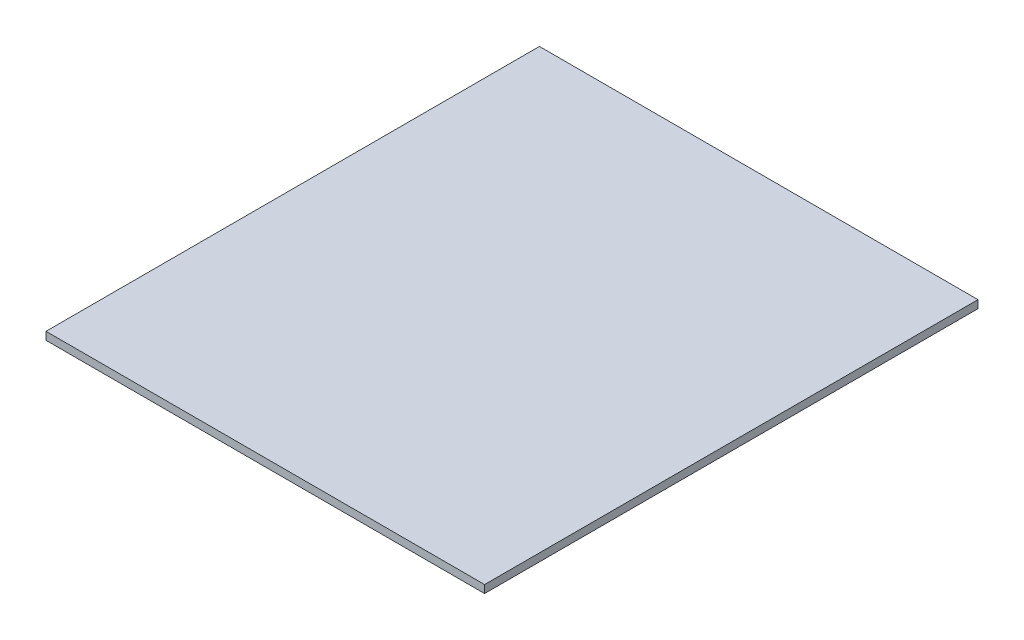
SolidWorks part; units mm, degrees
material "Maple"
ref_plane "Front Plane" through (0, 0, 0) normal (0, 0, 1) x (1, 0, 0)
ref_plane "Top Plane" through (0, 0, 0) normal (0, 1, 0) x (1, 0, 0)
ref_plane "Right Plane" through (0, 0, 0) normal (1, 0, 0) x (0, 0, -1)
sketch "Sketch1" plane through (0, 0, 0) normal (0, 1, 0) x (1, 0, 0)
  line L0 (355.6, 200.025) -> (0, 200.025) construction
  line L1 (0, 0) -> (355.6, 0)
  line L2 (0, 0) -> (0, 400.05)
  line L3 (0, 400.05) -> (355.6, 400.05)
  line L4 (355.6, 0) -> (355.6, 400.05)
  dimension "D1" = 400.05
  dimension "D2" = 355.6
extrude "Boss-Extrude1" add sketch "Sketch1" along normal blind 6.35
